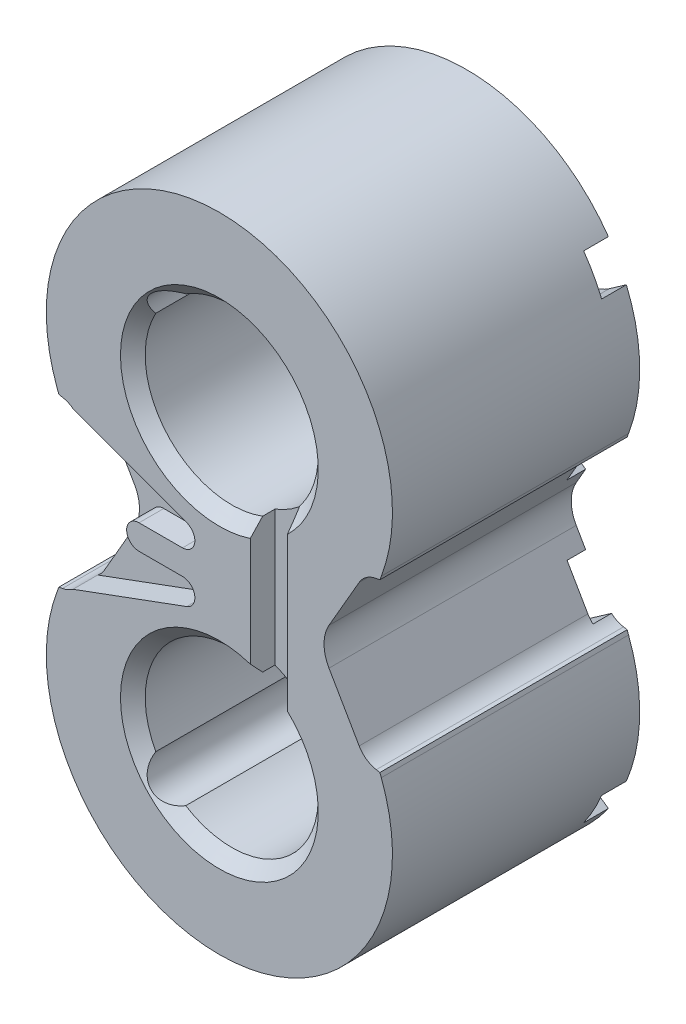
SolidWorks part; units mm, degrees
material "Aluminium"
ref_plane "Plan de face" through (0, 0, 0) normal (0, 0, 1) x (1, 0, 0)
ref_plane "Plan de dessus" through (0, 0, 0) normal (0, 1, 0) x (1, 0, 0)
ref_plane "Plan de droite" through (0, 0, 0) normal (1, 0, 0) x (0, 0, -1)
sketch "Esquisse1" plane through (0, 0, 0) normal (0, 0, 1) x (1, 0, 0)
  line L0 (0, -12) -> (0, 12) construction
  line L1 (-14, -12) -> (-14, 12)
  line L2 (14, 12) -> (14, -12)
  arc A0 (14, 12) -> (-14, 12) centre (0, 12) ccw
  arc A1 (-14, -12) -> (14, -12) centre (0, -12) ccw
  point P4 (0, 0)
  dimension "D1" = 24
  dimension "D2" = 28
extrude "Boss.-Extru.1" add sketch "Esquisse1" along normal blind 20
sketch "Esquisse2" plane through (0, 0, 20) normal (0, 0, 1) x (1, 0, 0)
  circle A0 centre (0, 12) radius 7
  circle A1 centre (0, -12) radius 7
  dimension "D1" = 14
extrude "Enlèv. mat.-Extru.1" cut sketch "Esquisse2" against normal through all
chamfer "Chanfrein1" distance 1 angle 45 2 edges at (7, -12, 20) (7, 12, 20)
sketch "Esquisse3" plane through (0, 0, 20) normal (0, 0, 1) x (1, 0, 0)
  line L0 (-14, 12) -> (-14, -12)
  line L1 (14, -12) -> (14, 12)
  arc A0 (7.2111, 0) -> (14, 12) centre (0, 12) ccw
  arc A1 (-7.2111, 0) -> (-14, -12) centre (0, -12) ccw
  arc A2 (14, 12) -> (-14, 12) centre (0, 12) ccw construction
  arc A3 (14, -12) -> (7.2111, 0) centre (0, -12) ccw
  arc A4 (-14, 12) -> (-7.2111, 0) centre (0, 12) ccw
extrude "Enlèv. mat.-Extru.3" cut sketch "Esquisse3" against normal through all
fillet "Congé1" radius 20 2 edges at (-7.2111, 0, 10) (7.2111, 0, 10)
sketch "Esquisse6" plane through (0, 0, 20) normal (0, 0, 1) x (1, 0, 0)
  line L0 (-12.9854, 6.75) -> (-11.7738, 6.5363)
  line L1 (-11.7738, 6.5363) -> (-8, 0)
  line L2 (-16.7192, 0) -> (14.8795, 0) construction
  line L3 (-12.9854, -6.75) -> (-11.7738, -6.5363)
  line L4 (-11.7738, -6.5363) -> (-8, 0)
  line L5 (-12.9854, -6.75) -> (-12.9854, 6.75)
  arc A0 (-13.099, -7.0588) -> (-13.099, 7.0588) centre (-31.8119, 0) ccw construction
  dimension "D1" = 13.5
  dimension "D2" = 8
  dimension "D3" = 130
  dimension "D4" = 60
extrude "Enlèv. mat.-Extru.4" cut sketch "Esquisse6" against normal through all
fillet "Congé2" radius 3 1 edges at (-8, 0, 10)
fillet "Congé3" radius 2 2 edges at (-11.7738, -6.5363, 10) (-11.7738, 6.5363, 10)
mirror "Symétrie1" about plane through (0, 0, 0) normal (1, 0, 0) of "Congé2", "Congé3", "Enlèv. mat.-Extru.4"
sketch "Esquisse7" plane through (0, 0, 20) normal (0, 0, 1) x (1, 0, 0)
  line L1 (5.5, -9.922) -> (2.5, -9.922)
  line L2 (5.5, -9.922) -> (5.5, 9.4418)
  line L3 (5.5, 9.4418) -> (2.5, 9.4418)
  line L4 (2.5, -9.922) -> (2.5, 9.4418)
  dimension "D1" = 3
  dimension "D2" = 2.5
extrude "Enlèv. mat.-Extru.5" cut sketch "Esquisse7" against normal blind 2
sketch "Esquisse8" plane through (0, 0, 20) normal (0, 0, 1) x (1, 0, 0)
  line L0 (-18.7202, 0) -> (14.2453, 0) construction
  line L1 (-4.25, -16) -> (-4.25, 16) construction
  circle A0 centre (-4.25, 16) radius 2
  circle A1 centre (-4.25, -16) radius 2
  point P6 (-4.25, 0)
  dimension "D2" = 4
  dimension "D1" = 32
  dimension "D3" = 4.25
extrude "Enlèv. mat.-Extru.6" cut sketch "Esquisse8" against normal through all
sketch "Esquisse9" plane through (0, 0, 20) normal (0, 0, 1) x (1, 0, 0)
  line L0 (-12.9854, 6.75) -> (-2.6388, 2.9384)
  line L1 (-19.9959, 0) -> (23.7195, 0) construction
  line L2 (-2.9845, 1) -> (-6.5, 1)
  line L3 (-2.9845, -1) -> (-6.5, -1)
  line L4 (-12.9854, -6.75) -> (-2.6388, -2.9384)
  line L5 (-12.9854, 6.75) -> (-12.9854, -6.75)
  arc A0 (-2.6388, 2.9384) -> (-2.9845, 1) centre (-2.9845, 2) cw
  arc A1 (-6.5, 1) -> (-6.5, -1) centre (-6.5, 0) ccw
  arc A2 (-2.6388, -2.9384) -> (-2.9845, -1) centre (-2.9845, -2) ccw
  point P13 (-2, 1.8244)
  dimension "D1" = 2
  dimension "D2" = 1
  dimension "D3" = 2
  dimension "D4" = 6.5
extrude "Enlèv. mat.-Extru.7" cut sketch "Esquisse9" against normal blind 2
sketch "Esquisse10" plane through (0, 0, 0) normal (0, 0, -1) x (-1, 0, 0)
  line L0 (-14.8806, 4.022) -> (-5.0508, 10.9049)
  line L3 (-12.5863, 0.7454) -> (-14.8806, 4.022)
  line L4 (14.1044, 2.7021) -> (8.1852, 6.1196)
  line L6 (9.1852, 7.8516) -> (15.1044, 4.4342)
  line L7 (15.1044, 4.4342) -> (14.1044, 2.7021)
  line L8 (0, 0) -> (-19.3278, 0) construction
  line L9 (0, 0) -> (0, 13.2195) construction
  line L10 (-13.7335, 2.3837) -> (0, 12) construction
  line L11 (0, 12) -> (14.6044, 3.5681) construction
  line L12 (-5.0508, 10.9049) -> (-2.7565, 7.6283)
  line L13 (8.1852, 6.1196) -> (9.1852, 7.8516)
  line L14 (-2.7565, 7.6283) -> (-12.5863, 0.7454)
  arc A0 (3.7214, 17.9289) -> (6.1433, 15.3555) centre (0, 12) ccw construction
  point P12 (0, 12)
  point P13 (-13.7335, 2.3837)
  point P16 (14.6044, 3.5681)
  point P20 (0, 12)
  dimension "D1" = 2
  dimension "D2" = 4
  dimension "D4" = 55
  dimension "D5" = 60
  dimension "D6" = 12
extrude "Enlèv. mat.-Extru.8" cut sketch "Esquisse10" against normal blind 1
mirror "Symétrie2" about plane through (0, 0, 0) normal (0, 1, 0) of "Enlèv. mat.-Extru.8"
sketch "Esquisse11" plane through (0, 0, 0) normal (0, 0, -1) x (-1, 0, 0)
  line L0 (-17.4651, 0) -> (18.8555, 0) construction
  line L1 (0, 12) -> (-16.5578, 23.5939) construction
  line L2 (0, 12) -> (0, 28.231) construction
  line L3 (-9.8213, 18.8769) -> (-11.4681, 20.0301)
  line L4 (-11.542, 16.4195) -> (-12.9225, 17.3861)
  line L5 (-12.9225, 17.3861) -> (-13.3224, 19.2865)
  line L6 (-13.3224, 19.2865) -> (-11.4681, 20.0301)
  line L7 (-3.5, 0) -> (-0.5, 0)
  arc A0 (0, 3.5) -> (-6.7536, 17.1613) centre (0, 12) ccw
  arc A1 (0, 0.5) -> (-9.1372, 18.9829) centre (0, 12) ccw
  arc A2 (0, 3.5) -> (-3.5, 0) centre (0, 0) ccw
  arc A3 (0, 0.5) -> (-0.5, 0) centre (0, 0) ccw
  arc A4 (3.7214, 17.9289) -> (-6.6422, 9.7906) centre (0, 12) ccw construction
  arc A5 (-9.8213, 18.8769) -> (-9.1372, 18.9829) centre (-9.5345, 19.2865) ccw
  arc A6 (-11.542, 16.4195) -> (-6.7536, 17.1613) centre (-9.5345, 19.2865) ccw
  arc A7 (13.099, 7.0588) -> (-13.099, 7.0588) centre (0, 12) ccw construction
  dimension "D1" = 3
  dimension "D2" = 1.5
  dimension "D3" = 55
extrude "Enlèv. mat.-Extru.9" cut sketch "Esquisse11" against normal blind 2
sketch "Esquisse12" plane through (0, 0, 1) normal (0, 0, -1) x (-1, 0, 0)
  line L0 (-11.7222, 6.2336) -> (-6.6422, 9.7906)
  line L1 (-6.6422, 9.7906) -> (-4.3479, 6.514)
  line L2 (-4.3479, 6.514) -> (-9.6268, 2.8177)
  line L3 (-9.6268, 2.8177) -> (-11.7222, 6.2336)
  line L4 (-9.6268, -2.8177) -> (-4.3479, -6.514)
  line L5 (-4.3479, -6.514) -> (-6.6422, -9.7906)
  line L6 (-6.6422, -9.7906) -> (-11.7222, -6.2336)
  line L7 (-11.7222, -6.2336) -> (-9.6268, -2.8177)
extrude "Enlèv. mat.-Extru.10" cut sketch "Esquisse12" against normal blind 0.5
mirror "Symétrie3" about plane through (0, 0, 0) normal (0, 1, 0) of "Enlèv. mat.-Extru.9"
